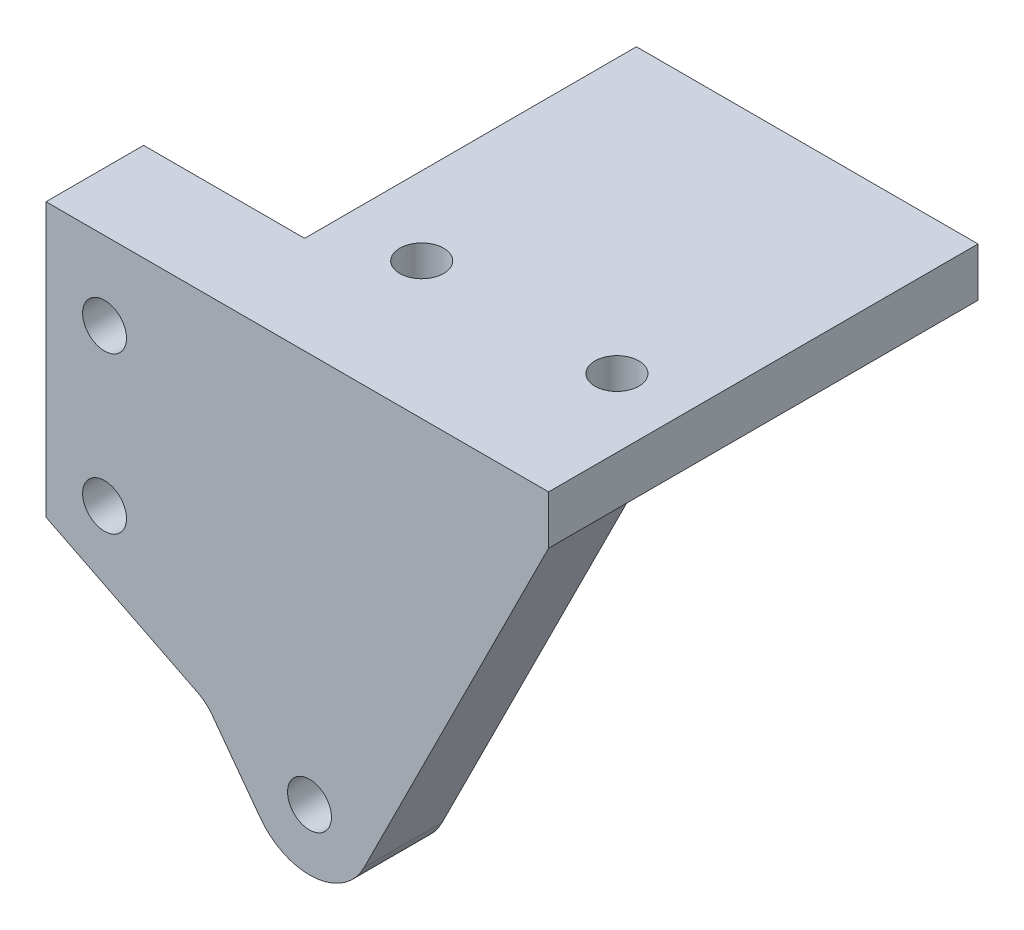
SolidWorks part; units mm, degrees
material "Printed PLA"
ref_plane "Front Plane" through (0, 0, 0) normal (0, 0, 1) x (1, 0, 0)
ref_plane "Top Plane" through (0, 0, 0) normal (0, 1, 0) x (1, 0, 0)
ref_plane "Right Plane" through (0, 0, 0) normal (1, 0, 0) x (0, 0, -1)
sketch "Sketch1" plane through (0, 0, 0) normal (0, 1, 0) x (1, 0, 0)
  line L1 (0, 0) -> (-26.5, 0)
  line L2 (0, 0) -> (0, 40)
  line L3 (0, 40) -> (-10, 40)
  line L4 (-26.5, 0) -> (-26.5, 10)
  line L7 (-26.5, 10) -> (-10, 10)
  line L8 (-10, 40) -> (-10, 10)
  dimension "D1" = 10
  dimension "D2" = 16.5
  dimension "D3" = 30
extrude "Boss-Extrude1" add sketch "Sketch1" along normal blind 28
sketch "Sketch2" plane through (-26.5, 0, 0) normal (-1, 0, 0) x (0, 0, 1)
  line L0 (0, 28) -> (0, 0)
  line L1 (0, 0) -> (8, 0)
  line L2 (8, 0) -> (8, 8)
  line L3 (8, 16) -> (8, 28)
  line L4 (8, 28) -> (0, 28)
  line L5 (-10, 28) -> (-10, 0) construction
  arc A0 (8, 8) -> (8, 16) centre (8, 12) cw
  dimension "D1" = 4
  dimension "D2" = 16
  dimension "D3" = 18
extrude "Boss-Extrude2" add sketch "Sketch2" against normal blind 12
sketch "Sketch3" plane through (0, 0, 8) normal (0, 0, 1) x (1, 0, 0)
  line L0 (-20.5, 4) -> (-20.5, 20) construction
  line L1 (-20.5, 4) -> (-20.5, 0) construction
  line L2 (-14.5, 0) -> (-26.5, 0) construction
  line L3 (-26.5, 12) -> (-20.5, 12) construction
  line L4 (-26.5, 16) -> (-26.5, 8) construction
  circle A0 centre (-20.5, 20) radius 2.25
  circle A1 centre (-20.5, 4) radius 2.25
  dimension "D1" = 4.5
  dimension "D2" = 16
extrude "Cut-Extrude1" cut sketch "Sketch3" against normal through all
sketch "Sketch4" plane through (0, 0, 0) normal (1, 0, 0) x (0, 0, -1)
  line L0 (34, 17.5) -> (22, 17.5) construction
  line L1 (0, 28) -> (40, 28) construction
  line L2 (40, 28) -> (40, 0) construction
  circle A0 centre (22, 17.5) radius 2.25 construction
  circle A1 centre (34, 17.5) radius 2.25
  dimension "D3" = 4.5
  dimension "D4" = 6
  dimension "D1" = 10.5
  dimension "D2" = 12
extrude "Cut-Extrude2" cut sketch "Sketch4" against normal through all
sketch "Sketch5" plane through (0, 0, 0) normal (1, 0, 0) x (0, 0, -1)
  line L0 (40, 28) -> (40, 0) construction
  line L1 (0, 28) -> (40, 28)
  line L2 (0, 28) -> (0, 23)
  line L3 (0, 23) -> (40, 23)
  line L4 (40, 28) -> (40, 23)
  dimension "D1" = 5
extrude "Boss-Extrude3" add sketch "Sketch5" along normal blind 25
sketch "Sketch6" plane through (0, 23, 0) normal (0, -1, 0) x (1, 0, 0)
  line L0 (25, 0) -> (25, -40) construction
  line L1 (25, 0) -> (0, 0) construction
  line L2 (-2, -14) -> (18, -14) construction
  circle A0 centre (-2, -14) radius 2.25
  circle A1 centre (18, -14) radius 2.25
  dimension "D1" = 7
  dimension "D2" = 14
  dimension "D3" = 4.5
  dimension "D4" = 20
extrude "Cut-Extrude3" cut sketch "Sketch6" along normal blind 10 and the other way through all
sketch "Sketch7" plane through (0, 0, 0) normal (1, 0, 0) x (0, 0, -1)
  line L0 (0, 23) -> (40, 23) construction
  line L1 (10.5, 23) -> (17.5, 23)
  line L2 (10.5, 23) -> (10.5, 18)
  line L3 (10.5, 18) -> (17.5, 18)
  line L4 (17.5, 23) -> (17.5, 18)
  line L5 (14, 18) -> (14, 13) construction
  line L6 (16.25, 13) -> (11.75, 13) construction
  dimension "D1" = 7
  dimension "D2" = 5
extrude "Cut-Extrude4" cut sketch "Sketch7" against normal blind 10
sketch "Sketch8" plane through (0, 0, 0) normal (0, 0, 1) x (1, 0, 0)
  line L0 (-14.5, 12) -> (0.5, 12) construction
  line L1 (-14.5, 8) -> (-14.5, 16) construction
  line L2 (0.5, 12) -> (0.5, -12) construction
  line L3 (-9.5, -9) -> (-4.5223, -15.7201)
  line L4 (6.0894, -14.7965) -> (25, 23)
  line L5 (25, 23) -> (0, 23)
  line L6 (0, 23) -> (0, 0)
  line L7 (0, 0) -> (-26.5, 0)
  line L9 (-26.5, 0) -> (-10.9225, -7.8046)
  circle A0 centre (0.5, -12) radius 2.25
  arc A1 (-4.5223, -15.7201) -> (6.0894, -14.7965) centre (0.5, -12) ccw
  arc A2 (-10.9225, -7.8046) -> (-9.5, -9) centre (-12.7143, -11.3809) cw
  dimension "D1" = 24
  dimension "D2" = 4.5
  dimension "D4" = 4
  dimension "D5" = 4
  dimension "D7" = 10
  dimension "D3" = 15
  dimension "D6" = 3
extrude "Boss-Extrude4" add sketch "Sketch8" against normal blind 8
sketch "Sketch9" plane through (0, 0, -40) normal (0, 0, -1) x (-1, 0, 0)
  line L0 (-25, 23) -> (0, 0)
  line L1 (0, 0) -> (0, 23) construction
  line L2 (0, 23) -> (-25, 23) construction
  line L3 (0, 0) -> (10, 0)
  line L4 (10, 0) -> (10, 28)
  line L5 (10, 28) -> (-25, 28)
  line L6 (-25, 28) -> (-25, 23)
extrude "Boss-Extrude6" add sketch "Sketch9" along normal blind 4
sketch "Sketch10" plane through (-14.5, 0, 0) normal (1, 0, 0) x (0, 0, -1)
  line L1 (-8, 28) -> (0, 28)
  line L2 (-8, 28) -> (-8, 0)
  line L3 (-8, 0) -> (0, 0)
  line L4 (0, 28) -> (0, 0)
extrude "Cut-Extrude5" cut sketch "Sketch10" against normal through all
